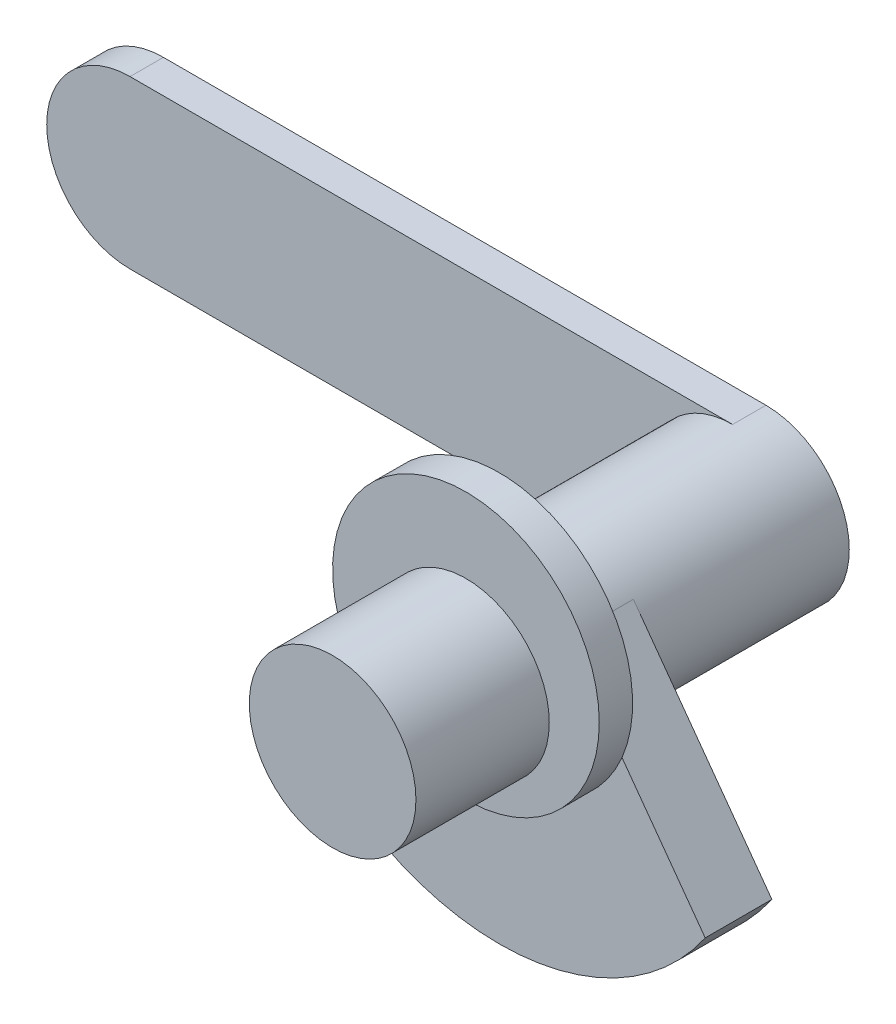
SolidWorks part; units mm, degrees
ref_plane "Front Plane" through (0, 0, 0) normal (0, 0, 1) x (1, 0, 0)
ref_plane "Top Plane" through (0, 0, 0) normal (0, 1, 0) x (1, 0, 0)
ref_plane "Right Plane" through (0, 0, 0) normal (1, 0, 0) x (0, 0, -1)
sketch "Sketch2" plane through (0, 0, 0) normal (0, 0, 1) x (1, 0, 0)
  line L0 (0, 63.5) -> (-459.1356, 63.5)
  line L1 (0, -63.5) -> (-459.1356, -63.5)
  line L2 (-459.1356, 63.5) -> (-459.1356, -63.5) construction
  arc A1 (-459.1356, 63.5) -> (-459.1356, -63.5) centre (-459.1356, 0) ccw
  arc A2 (0, 63.5) -> (0, -63.5) centre (0, 0) cw
  point P7 (-459.1356, 0)
extrude "Boss-Extrude1" add sketch "Sketch2" along normal blind 25.4 contours L0 A1 L1 A2
sketch "Sketch3" plane through (0, 0, 25.4) normal (0, 0, 1) x (1, 0, 0)
  circle A0 centre (0, 0) radius 63.5
extrude "Boss-Extrude2" add sketch "Sketch3" along normal blind 127
sketch "Sketch4" plane through (0, 0, 152.4) normal (0, 0, 1) x (1, 0, 0)
  line L0 (-51.3726, 37.3244) -> (-156.9206, -107.95)
  line L2 (51.3726, 37.3244) -> (156.9206, -107.95)
  circle A0 centre (0, 0) radius 63.5 construction
  arc A1 (-51.3726, 37.3244) -> (51.3726, 37.3244) centre (0, 0) cw
  arc A2 (-156.9206, -107.95) -> (156.9206, -107.95) centre (0, 0.0601) ccw
  point P9 (-149.8741, -107.95)
  dimension "D3" = 190.5
  dimension "D1" = 107.95
  dimension "D2" = 72
extrude "Boss-Extrude3" add sketch "Sketch4" along normal blind 50.8
sketch "Sketch5" plane through (0, 0, 203.2) normal (0, 0, 1) x (1, 0, 0)
  line L0 (0, 0) -> (0, 19.05) construction
  circle A0 centre (0, 0) radius 63.5 construction
  circle A1 centre (0, 19.05) radius 101.6
extrude "Boss-Extrude4" add sketch "Sketch5" along normal blind 25.4
sketch "Sketch6" plane through (0, 0, 228.6) normal (0, 0, 1) x (1, 0, 0)
  circle A0 centre (0, 0) radius 63.5
extrude "Boss-Extrude5" add sketch "Sketch6" along normal blind 101.6
